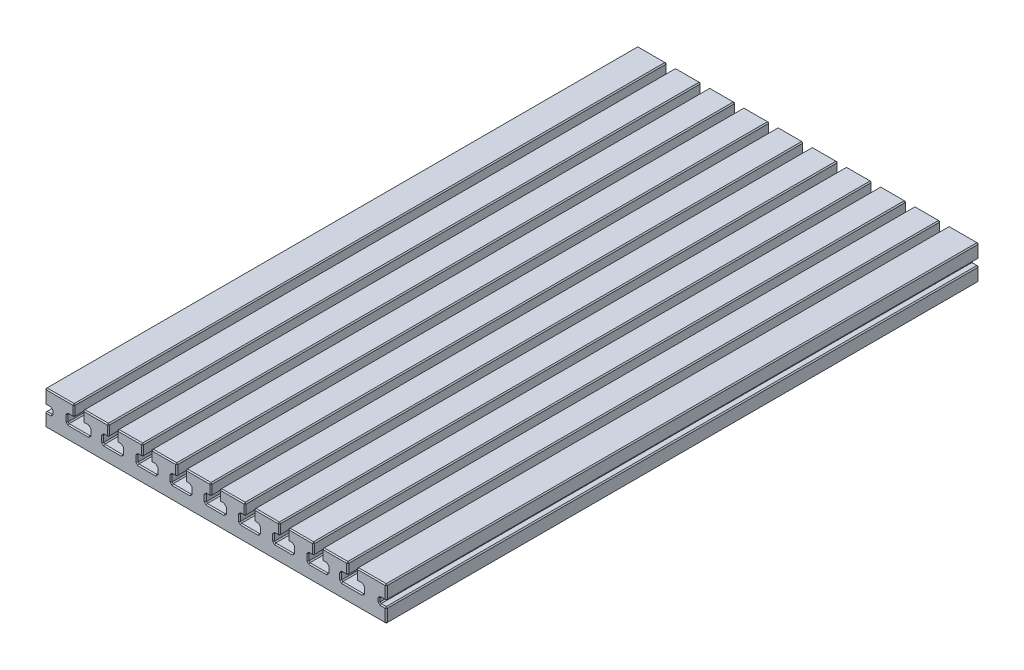
SolidWorks part; units mm, degrees
ref_plane "Plane1" through (0, 0, 0) normal (0, 0, 1) x (1, 0, 0)
ref_plane "Plane2" through (0, 0, 0) normal (0, 1, 0) x (1, 0, 0)
ref_plane "Plane3" through (0, 0, 0) normal (1, 0, 0) x (0, 0, -1)
sketch "Sketch1" plane through (0, 0, 0) normal (0, 0, 1) x (1, 0, 0)
  line L1 (-379.4125, 0) -> (381, 0)
  line L2 (-379.4125, 0) -> (-379.4125, -76.2)
  line L3 (-379.4125, -76.2) -> (381, -76.2)
  line L4 (381, 0) -> (381, -76.2)
extrude "Base-Extrude" add sketch "Sketch1" against normal blind 1320.8
sketch "Sketch2" plane through (0, 0, 0) normal (0, 0, 1) x (1, 0, 0)
  line L0 (381, 0) -> (-379.4125, 0) construction
  line L1 (-9.525, 0) -> (9.525, 0)
  line L2 (-9.525, 0) -> (-9.525, -25.4)
  line L3 (9.525, -25.4) -> (22.225, -25.4)
  line L4 (9.525, 0) -> (9.525, -25.4)
  line L5 (85.725, -25.4) -> (98.425, -25.4)
  line L6 (-22.225, -25.4) -> (-9.525, -25.4)
  line L7 (-22.225, -25.4) -> (-22.225, -44.45)
  line L8 (-22.225, -44.45) -> (22.225, -44.45)
  line L9 (22.225, -25.4) -> (22.225, -44.45)
  line L10 (66.675, 0) -> (85.725, 0)
  line L11 (66.675, 0) -> (66.675, -25.4)
  line L12 (161.925, -25.4) -> (174.625, -25.4)
  line L13 (85.725, 0) -> (85.725, -25.4)
  line L14 (53.975, -25.4) -> (66.675, -25.4)
  line L15 (53.975, -25.4) -> (53.975, -44.45)
  line L16 (53.975, -44.45) -> (98.425, -44.45)
  line L17 (98.425, -25.4) -> (98.425, -44.45)
  line L18 (142.875, 0) -> (161.925, 0)
  line L19 (142.875, 0) -> (142.875, -25.4)
  line L20 (-66.675, -25.4) -> (-53.975, -25.4)
  line L21 (161.925, 0) -> (161.925, -25.4)
  line L22 (130.175, -25.4) -> (142.875, -25.4)
  line L23 (130.175, -25.4) -> (130.175, -44.45)
  line L24 (130.175, -44.45) -> (174.625, -44.45)
  line L25 (174.625, -25.4) -> (174.625, -44.45)
  line L26 (-85.725, 0) -> (-66.675, 0)
  line L27 (-85.725, 0) -> (-85.725, -25.4)
  line L28 (-142.875, -25.4) -> (-130.175, -25.4)
  line L29 (-66.675, 0) -> (-66.675, -25.4)
  line L30 (-98.425, -25.4) -> (-85.725, -25.4)
  line L31 (-98.425, -25.4) -> (-98.425, -44.45)
  line L32 (-98.425, -44.45) -> (-53.975, -44.45)
  line L33 (-53.975, -25.4) -> (-53.975, -44.45)
  line L34 (-161.925, 0) -> (-142.875, 0)
  line L35 (-161.925, 0) -> (-161.925, -25.4)
  line L36 (-219.075, -25.4) -> (-206.375, -25.4)
  line L37 (-142.875, 0) -> (-142.875, -25.4)
  line L38 (-174.625, -25.4) -> (-161.925, -25.4)
  line L39 (-174.625, -25.4) -> (-174.625, -44.45)
  line L40 (-174.625, -44.45) -> (-130.175, -44.45)
  line L41 (-130.175, -25.4) -> (-130.175, -44.45)
  line L42 (381, -31.3382) -> (365.125, -31.3382)
  line L43 (381, -31.3382) -> (381, -44.0382)
  line L44 (381, -44.0382) -> (365.125, -44.0382)
  line L45 (365.125, -31.3382) -> (365.125, -44.0382)
  line L46 (-379.4125, -32.5488) -> (-363.5375, -32.5488)
  line L47 (-379.4125, -32.5488) -> (-379.4125, -45.2488)
  line L48 (-379.4125, -45.2488) -> (-363.5375, -45.2488)
  line L49 (-363.5375, -32.5488) -> (-363.5375, -45.2488)
  line L50 (-238.125, 0) -> (-219.075, 0)
  line L51 (-238.125, 0) -> (-238.125, -25.4)
  line L52 (238.125, -25.4) -> (250.825, -25.4)
  line L53 (-219.075, 0) -> (-219.075, -25.4)
  line L54 (-250.825, -25.4) -> (-238.125, -25.4)
  line L55 (-250.825, -25.4) -> (-250.825, -44.45)
  line L56 (-250.825, -44.45) -> (-206.375, -44.45)
  line L57 (-206.375, -25.4) -> (-206.375, -44.45)
  line L58 (219.075, 0) -> (238.125, 0)
  line L59 (219.075, 0) -> (219.075, -25.4)
  line L60 (-295.275, -25.4) -> (-279.4, -25.4)
  line L61 (238.125, 0) -> (238.125, -25.4)
  line L62 (206.375, -25.4) -> (219.075, -25.4)
  line L63 (206.375, -25.4) -> (206.375, -44.45)
  line L64 (206.375, -44.45) -> (250.825, -44.45)
  line L65 (250.825, -25.4) -> (250.825, -44.45)
  line L66 (-314.325, 0) -> (-295.275, 0)
  line L67 (-314.325, 0) -> (-314.325, -25.4)
  line L68 (314.325, -25.4) -> (330.2017, -25.4)
  line L69 (-295.275, 0) -> (-295.275, -25.4)
  line L70 (-330.2, -25.4) -> (-314.325, -25.4)
  line L71 (-330.2, -25.4) -> (-330.2, -44.45)
  line L72 (-330.2, -44.45) -> (-279.4, -44.45)
  line L73 (-279.4, -25.4) -> (-279.4, -44.45)
  line L74 (295.275, 0) -> (314.325, 0)
  line L75 (295.275, 0) -> (295.275, -25.4)
  line L77 (314.325, 0) -> (314.325, -25.4)
  line L78 (279.4, -25.4) -> (295.275, -25.4)
  line L79 (279.4, -25.4) -> (279.4, -44.45)
  line L80 (279.4, -44.45) -> (330.2017, -44.45)
  line L81 (330.2017, -25.4) -> (330.2017, -44.45)
extrude "Cut-Extrude1" cut sketch "Sketch2" against normal blind 1320.8
chamfer "Chamfer1" distance 2.3622 angle 45
sketch "Sketch3" plane through (0, 0, 0) normal (0, 1, 0) x (-1, 0, 0)
  circle A0 centre (0, -663.575) radius 38.1
  dimension "D1" = 76.2
extrude "Cut-Extrude2" [suppressed] cut sketch "Sketch3" against normal blind 50.8
